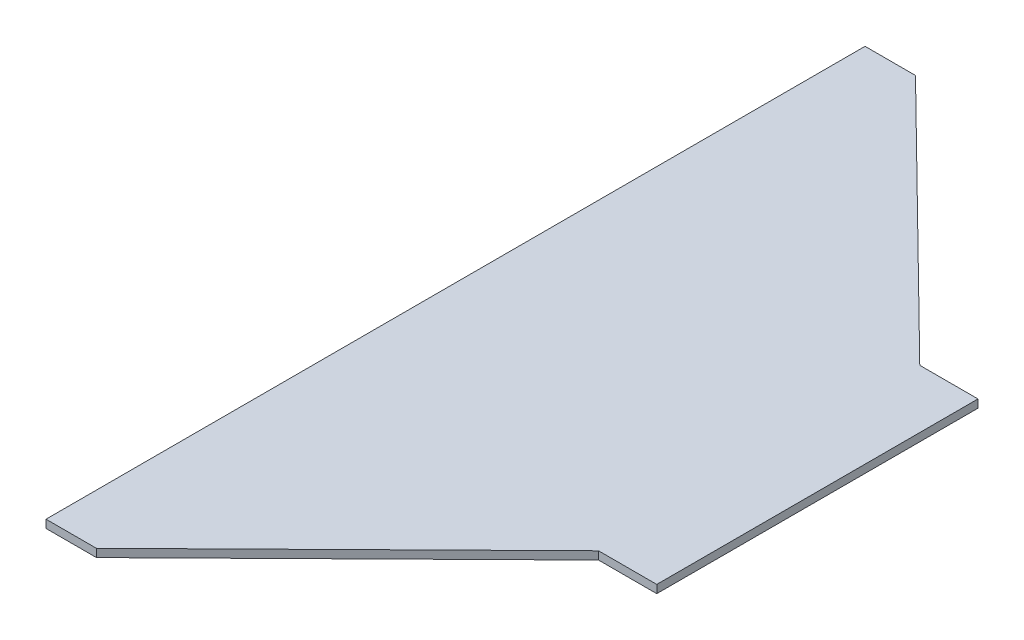
SolidWorks part; units mm, degrees
ref_plane "Front Plane" through (0, 0, 0) normal (0, 0, 1) x (1, 0, 0)
ref_plane "Top Plane" through (0, 0, 0) normal (0, 1, 0) x (1, 0, 0)
ref_plane "Right Plane" through (0, 0, 0) normal (1, 0, 0) x (0, 0, -1)
sketch "Croquis1" plane through (0, 0, 0) normal (0, 1, 0) x (1, 0, 0)
  line L0 (0, 0) -> (0, -101.83)
  line L1 (0, -101.83) -> (6.27, -101.83)
  line L3 (6.27, -101.83) -> (37.7489, -70.885)
  line L4 (37.7489, -70.885) -> (44.9889, -70.885)
  line L5 (44.9889, -70.885) -> (44.9889, -30.945)
  line L6 (44.9889, -30.945) -> (37.7489, -30.945)
  line L7 (37.7489, -30.945) -> (6.27, 0)
  line L9 (6.27, 0) -> (0, 0)
  point P3 (3, -103.0717)
  point P5 (3, -0.0298)
  point P10 (3, -102.91)
  point P12 (44.9889, -50.915)
  point P13 (0, -50.915)
  point P14 (3, -102.9289)
  point P15 (3, -103.1513)
  point P16 (0, 0)
  point P18 (17.8095, -100.7422)
  dimension "D1" = 6.27
  dimension "D2" = 101.83
  dimension "D3" = 135.49
  dimension "D5" = 7.24
  dimension "D6" = 39.94
extrude "Saliente-Extruir1" add sketch "Croquis1" along normal blind 1
